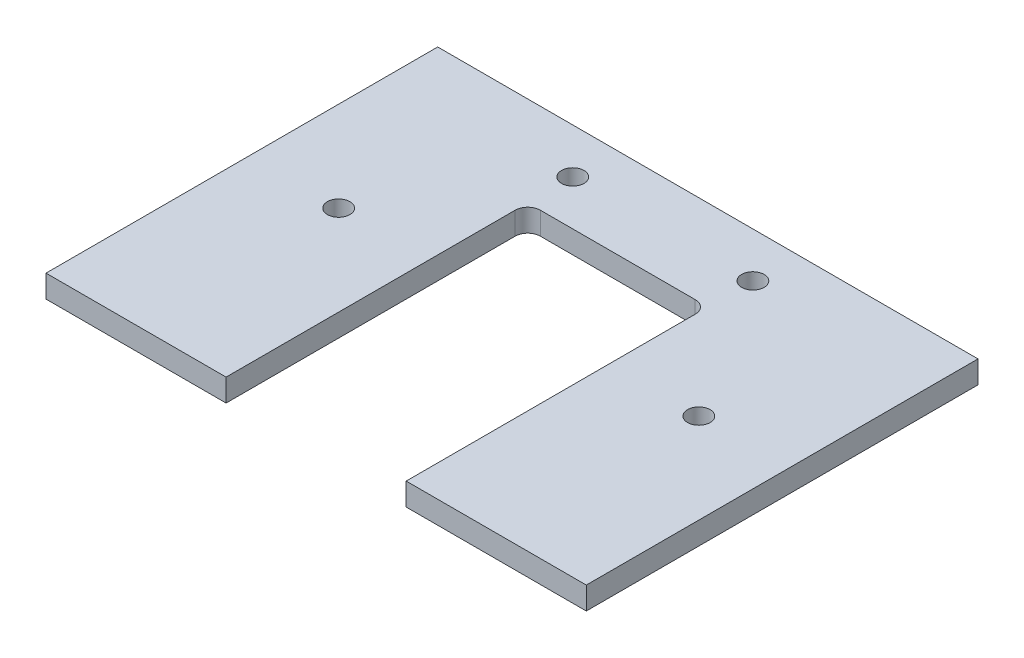
SolidWorks part; units mm, degrees
material "1060 Alloy"
ref_plane "Front Plane" through (0, 0, 0) normal (0, 0, 1) x (1, 0, 0)
ref_plane "Top Plane" through (0, 0, 0) normal (0, 1, 0) x (1, 0, 0)
ref_plane "Right Plane" through (0, 0, 0) normal (1, 0, 0) x (0, 0, -1)
sketch "Sketch1" plane through (0, 0, 0) normal (0, 1, 0) x (1, 0, 0)
  line L0 (-38.1, -42.545) -> (38.1, -42.545) construction
  line L1 (0, 0) -> (0, 12.7) construction
  line L2 (-12.7, -0.889) -> (-38.1, -0.889) construction
  line L3 (38.1, 12.7) -> (-38.1, 12.7)
  line L4 (-38.1, 12.7) -> (-38.1, -42.545)
  line L5 (-38.1, -42.545) -> (-12.7, -42.545)
  line L6 (0, 6.35) -> (-38.1, 6.35) construction
  line L7 (38.1, -0.889) -> (-38.1, -0.889) construction
  line L8 (-12.7, -42.545) -> (-12.7, 0)
  line L9 (-12.7, 0) -> (12.7, 0)
  line L10 (38.1, 12.7) -> (38.1, -42.545)
  line L11 (38.1, -42.545) -> (12.7, -42.545)
  line L12 (12.7, -42.545) -> (12.7, 0)
  line L13 (-38.1, -27.051) -> (-12.7, -27.051) construction
  line L14 (-38.1, -27.051) -> (38.1, -27.051) construction
  line L15 (-25.4, -0.889) -> (-25.4, -27.051) construction
  line L18 (38.1, 12.7) -> (-38.1, 12.7) construction
  circle A0 centre (-25.4, -13.97) radius 1.5875
  circle A2 centre (25.4, -13.97) radius 1.5875
  circle A3 centre (-12.7, 6.35) radius 1.5875
  circle A4 centre (12.7, 6.35) radius 1.5875
  dimension "D4" = 3.175
  dimension "D1" = 25.4
  dimension "D3" = 12.7
extrude "Boss-Extrude1" add sketch "Sketch1" along normal blind 3.175
fillet "Fillet1" radius 1.778 2 edges at (12.7, 1.5875, 0) (-12.7, 1.5875, 0)
